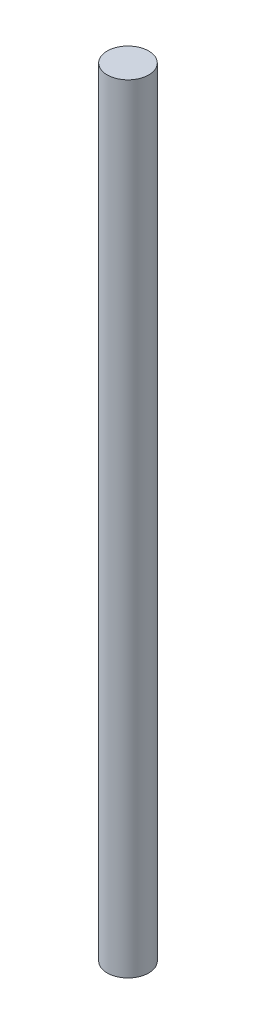
SolidWorks part; units mm, degrees
ref_plane "Front Plane" through (0, 0, 0) normal (0, 0, 1) x (1, 0, 0)
ref_plane "Top Plane" through (0, 0, 0) normal (0, 1, 0) x (1, 0, 0)
ref_plane "Right Plane" through (0, 0, 0) normal (1, 0, 0) x (0, 0, -1)
sketch "Sketch1" plane through (0, 0, 0) normal (0, 1, 0) x (1, 0, 0)
  circle A0 centre (0, 0) radius 4
  dimension "D1" = 8
extrude "Boss-Extrude1" add sketch "Sketch1" along normal blind 150 contours A0
